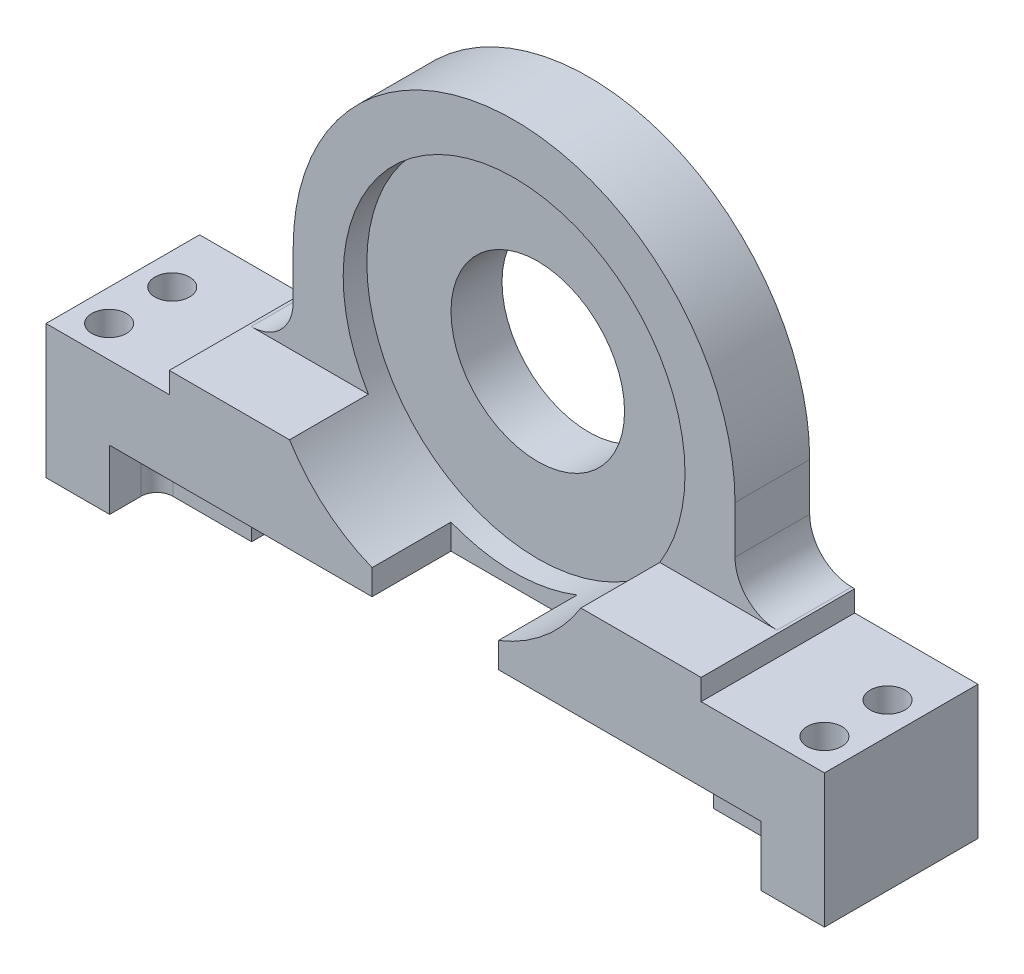
SolidWorks part; units mm, degrees
ref_plane "Front Plane" through (0, 0, 0) normal (0, 0, 1) x (1, 0, 0)
ref_plane "Top Plane" through (0, 0, 0) normal (0, 1, 0) x (1, 0, 0)
ref_plane "Right Plane" through (0, 0, 0) normal (1, 0, 0) x (0, 0, -1)
sketch "Sketch2" plane through (0, 0, 0) normal (0, 0, 1) x (1, 0, 0)
  line L0 (-21, 0) -> (21, 0)
  line L1 (-21, 14.7) -> (-21, 23.2)
  line L2 (21, 23.2) -> (21, 14.7)
  line L3 (21, 14.7) -> (37, 14.7)
  line L4 (37, 14.7) -> (37, 0)
  line L9 (37, 0) -> (21, 0)
  line L10 (0, 9.4378) -> (0, -16.7527) construction
  line L11 (-37, 0) -> (-21, 0)
  line L12 (-37, 14.7) -> (-37, 0)
  line L13 (-21, 14.7) -> (-37, 14.7)
  circle A1 centre (0, 23.2) radius 16
  arc A3 (-21, 23.2) -> (21, 23.2) centre (0, 23.2) cw
  point P2 (0, 44.2)
  point P7 (0, 0)
  point P8 (0, 0.9)
  point P10 (0, 7.2)
  point P12 (0, 39.2)
  dimension "D1" = 32
  dimension "D6" = 23.2
  dimension "D2" = 14.7
  dimension "D3" = 16
  dimension "D5" = 5
extrude "Boss-Extrude1" add sketch "Sketch2" along normal blind 12
sketch "Sketch3" plane through (0, 0, 0) normal (0, 0, 1) x (1, 0, 0)
  circle A1 centre (0, 23.2) radius 8.25
  circle A2 centre (0, 23.2) radius 16 construction
  circle A3 centre (0, 23.2) radius 16
  dimension "D1" = 16.5
extrude "Boss-Extrude2" add sketch "Sketch3" along normal blind 2.5
sketch "Sketch8" plane through (0, 0, 0) normal (0, 0, 1) x (1, 0, 0)
  line L0 (26.9, 8.35) -> (26.9, 7) construction
  line L1 (-27.15, 0) -> (27.15, 0)
  line L3 (-27.15, 10.7) -> (27.15, 10.7)
  line L4 (27.15, 7.35) -> (27.15, 10.7)
  line L5 (27.15, 7.35) -> (34.2, 7.35)
  line L6 (34.2, 7.35) -> (34.2, 0)
  line L7 (-37, 0) -> (37, 0) construction
  line L8 (0, 0) -> (0, 10.7) construction
  line L9 (26.9, 7) -> (33.9, 7) construction
  line L10 (33.9, 0) -> (33.9, 7) construction
  line L11 (24.9, 10.35) -> (-24.9, 10.35) construction
  line L12 (34.2, 0) -> (27.15, 0)
  line L13 (-34.2, 0) -> (-27.15, 0)
  line L14 (-34.2, 7.35) -> (-34.2, 0)
  line L15 (-27.15, 7.35) -> (-34.2, 7.35)
  line L16 (-27.15, 7.35) -> (-27.15, 10.7)
  point P6 (0, 10.7)
  dimension "D1" = 0.25
  dimension "D2" = 0.35
  dimension "D3" = 0.35
  dimension "D4" = 0.3
extrude "Cut-Extrude4" cut sketch "Sketch8" along normal blind 1
sketch "Sketch9" plane through (0, 0, 1) normal (0, 0, -1) x (-1, 0, 0)
  line L0 (-34.2, 0) -> (34.2, 0) construction
  line L1 (21.95, 0) -> (-21.95, 0)
  line L2 (21.95, 0) -> (21.95, 5.7)
  line L3 (21.95, 5.7) -> (-21.95, 5.7)
  line L4 (-21.95, 0) -> (-21.95, 5.7)
  line L5 (-27.15, 7.35) -> (-27.15, 10.7) construction
  point P6 (0, 5.7)
  dimension "D1" = 5.2
  dimension "D2" = 5.7
extrude "Cut-Extrude5" cut sketch "Sketch9" against normal up to next
sketch "Sketch10" plane through (0, 0, 0) normal (0, -1, 0) x (1, 0, 0)
  line L0 (-37, 12) -> (-21.95, 12) construction
  line L1 (-37, 12) -> (-37, 0) construction
  line L2 (0, 0) -> (0, 15.6223) construction
  line L3 (-37, 0) -> (-34.2, 0) construction
  circle A0 centre (-34, 9) radius 1.65
  circle A1 centre (-34, 3) radius 1.65
  circle A2 centre (34, 3) radius 1.65
  circle A3 centre (34, 9) radius 1.65
  dimension "D1" = 3.3
  dimension "D4" = 3
  dimension "D2" = 3
  dimension "D3" = 3
extrude "Cut-Extrude6" cut sketch "Sketch10" against normal through all
sketch "Sketch11" plane through (0, 0, 12) normal (0, 0, 1) x (1, 0, 0)
  line L0 (21, 14.7) -> (21, 23.2) construction
  line L1 (-21, 23.2) -> (-21, 14.7) construction
  line L2 (21, 14.7) -> (21, 23.2)
  line L3 (-21, 23.2) -> (-21, 14.7)
  line L4 (-21, 14.7) -> (21, 14.7)
  arc A0 (21, 23.2) -> (-21, 23.2) centre (0, 23.2) ccw construction
  arc A1 (21, 23.2) -> (-21, 23.2) centre (0, 23.2) ccw
extrude "Cut-Extrude7" cut sketch "Sketch11" against normal offset from surface (7.5 mm away) 2 up to face at (16, 23.2, 2.5)
fillet "Filete1" radius 2 2 edges at (27.15, 10.7, 0.5) (-27.15, 10.7, 0.5)
fillet "Filete2" radius 4 2 edges at (-21, 14.7, 2.25) (21, 14.7, 2.25)
sketch "Sketch12" plane through (0, 0, 12) normal (0, 0, 1) x (1, 0, 0)
  line L0 (21.95, 5.7) -> (-21.95, 5.7) construction
  line L1 (21.95, 0) -> (30.95, 0)
  line L2 (21.95, 0) -> (21.95, 5.7)
  line L3 (21.95, 5.7) -> (30.95, 5.7)
  line L4 (30.95, 0) -> (30.95, 5.7)
  line L5 (0, 0) -> (0, 5.354) construction
  line L6 (-30.95, 0) -> (-30.95, 5.7)
  line L7 (-21.95, 5.7) -> (-30.95, 5.7)
  line L8 (-21.95, 0) -> (-21.95, 5.7)
  line L9 (-21.95, 0) -> (-30.95, 0)
  dimension "D1" = 9
extrude "Cut-Extrude8" cut sketch "Sketch12" against normal blind 4.5
sketch "Sketch14" plane through (0, 0, 7.5) normal (0, 0, 1) x (1, 0, 0)
  line L1 (23.95, 1.35) -> (30.95, 1.35)
  line L2 (23.95, 1.35) -> (23.95, 4.35)
  line L3 (23.95, 4.35) -> (30.95, 4.35)
  line L4 (30.95, 1.35) -> (30.95, 4.35)
  line L5 (30.95, 0) -> (30.95, 5.7) construction
  line L6 (30.95, 0) -> (30.95, 5.7) construction
  line L7 (0, 0) -> (0, 5.8267) construction
  line L8 (-30.95, 1.35) -> (-30.95, 4.35)
  line L9 (-23.95, 4.35) -> (-30.95, 4.35)
  line L10 (-23.95, 1.35) -> (-23.95, 4.35)
  line L11 (-23.95, 1.35) -> (-30.95, 1.35)
  point P8 (30.95, 2.85)
  point P9 (-30.95, 2.85)
  dimension "D1" = 3
  dimension "D2" = 7
extrude "Cut-Extrude9" [suppressed] cut sketch "Sketch14" against normal blind 1.5
fillet "Fillet1" [suppressed] radius 1.5
sketch "Sketch15" plane through (0, 0, 12) normal (0, 0, 1) x (1, 0, 0)
  line L0 (30.95, 5.7) -> (-30.95, 5.7) construction
  line L1 (-6, 5.7) -> (6, 5.7)
  line L2 (-6, 5.7) -> (-6, 8.3676)
  line L3 (-6, 8.3676) -> (6, 8.3676)
  line L4 (6, 5.7) -> (6, 8.3676)
  arc A0 (-13.5554, 14.7) -> (13.5554, 14.7) centre (0, 23.2) ccw construction
  point P6 (0, 8.3676)
  dimension "D1" = 12
extrude "Cut-Extrude10" cut sketch "Sketch15" against normal up to surface (7.5 mm away) up to face at (0, 23.3054, 4.5)
sketch "Sketch16" plane through (0, 0, 0) normal (0, 0, -1) x (-1, 0, 0)
  line L1 (-37, 0) -> (-37, 14.7) construction
  line L3 (-25.15, 10.7) -> (25.15, 10.7) construction
  line L4 (-37, 14.7) -> (-25, 14.7)
  line L5 (-34.2, 0) -> (-37, 0) construction
  line L6 (-34.2, 0) -> (-34.2, 7.35) construction
  line L7 (-34.2, 7.35) -> (-27.15, 7.35) construction
  line L8 (-27.15, 7.35) -> (-27.15, 8.7) construction
  line L9 (27.15, 8.7) -> (27.15, 7.35) construction
  line L10 (27.15, 7.35) -> (34.2, 7.35) construction
  line L11 (34.2, 7.35) -> (34.2, 0) construction
  line L12 (37, 0) -> (34.2, 0) construction
  line L13 (37, 0) -> (34.2, 0)
  line L14 (34.2, 7.35) -> (34.2, 0)
  line L15 (27.15, 7.35) -> (34.2, 7.35)
  line L16 (27.15, 8.7) -> (27.15, 7.35)
  line L17 (-25.15, 10.7) -> (25.15, 10.7)
  line L18 (-27.15, 7.35) -> (-27.15, 8.7)
  line L19 (-34.2, 7.35) -> (-27.15, 7.35)
  line L20 (-34.2, 0) -> (-34.2, 7.35)
  line L21 (-34.2, 0) -> (-37, 0)
  line L22 (-37, 14.7) -> (-37, 0)
  line L23 (37, 14.7) -> (37, 0)
  line L24 (25, 14.7) -> (37, 14.7) construction
  line L25 (21, 23.2) -> (21, 18.7) construction
  line L26 (-21, 18.7) -> (-21, 23.2) construction
  line L27 (25, 14.7) -> (37, 14.7)
  line L28 (21, 23.2) -> (21, 18.7)
  line L29 (-21, 18.7) -> (-21, 23.2)
  arc A0 (-25.15, 10.7) -> (-27.15, 8.7) centre (-25.15, 8.7) ccw construction
  arc A1 (27.15, 8.7) -> (25.15, 10.7) centre (25.15, 8.7) ccw construction
  arc A2 (27.15, 8.7) -> (25.15, 10.7) centre (25.15, 8.7) ccw
  arc A3 (-25.15, 10.7) -> (-27.15, 8.7) centre (-25.15, 8.7) ccw
  arc A4 (21, 18.7) -> (25, 14.7) centre (25, 18.7) ccw construction
  arc A5 (21, 23.2) -> (-21, 23.2) centre (0, 23.2) ccw construction
  arc A6 (-25, 14.7) -> (-21, 18.7) centre (-25, 18.7) ccw construction
  arc A7 (21, 18.7) -> (25, 14.7) centre (25, 18.7) ccw
  arc A8 (21, 23.2) -> (-21, 23.2) centre (0, 23.2) ccw
  arc A9 (-25, 14.7) -> (-21, 18.7) centre (-25, 18.7) ccw
  circle A10 centre (0, 23.2) radius 8.25 construction
  circle A11 centre (0, 23.2) radius 8.25
extrude "Boss-Extrude3" add sketch "Sketch16" along normal blind 2.6
fillet "Fillet2" radius 1.5 2 edges at (-30.95, 2.85, 7.5) (30.95, 2.85, 7.5)
sketch "Sketch17" plane through (0, 0, 12) normal (0, 0, 1) x (1, 0, 0)
  line L0 (-13.5554, 14.7) -> (-37, 14.7) construction
  line L1 (-37, 14.7) -> (-25.2777, 14.7)
  line L2 (-37, 14.7) -> (-37, 12.7)
  line L3 (-37, 12.7) -> (-25.2777, 12.7)
  line L4 (-25.2777, 14.7) -> (-25.2777, 12.7)
  line L5 (0, 0) -> (0, 26.1143) construction
  line L6 (25.2777, 14.7) -> (25.2777, 12.7)
  line L7 (37, 12.7) -> (25.2777, 12.7)
  line L8 (37, 14.7) -> (37, 12.7)
  line L9 (37, 14.7) -> (25.2777, 14.7)
  dimension "D1" = 2
extrude "Cut-Extrude11" cut sketch "Sketch17" against normal up to next
sketch "Sketch18" plane through (0, 0, 4.5) normal (0, 0, 1) x (1, 0, 0)
  circle A0 centre (0, 23.2) radius 16.25
  arc A1 (13.5554, 14.7) -> (-13.5554, 14.7) centre (0, 23.2) ccw construction
  dimension "D1" = 0.25
extrude "Cut-Extrude12" cut sketch "Sketch18" against normal offset from surface 0.25 and the other way up to next
